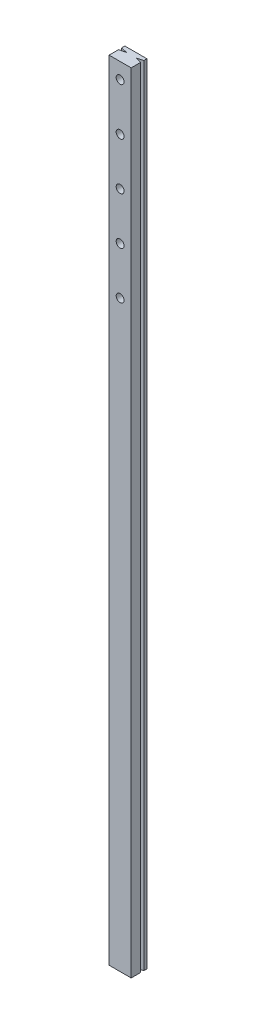
SolidWorks part; units mm, degrees
ref_plane "前视基准面" through (0, 0, 0) normal (0, 0, 1) x (1, 0, 0)
ref_plane "上视基准面" through (0, 0, 0) normal (0, 1, 0) x (1, 0, 0)
ref_plane "右视基准面" through (0, 0, 0) normal (1, 0, 0) x (0, 0, -1)
sketch "草图1" plane through (0, 0, 0) normal (0, 1, 0) x (1, 0, 0)
  line L0 (-89.2543, 0) -> (77.4586, 0) construction
  line L1 (0, 99.6738) -> (0, -95.7419) construction
  line L2 (-3.5, 1.5) -> (-1.5, 1)
  line L3 (-3.5, -2.5) -> (3.5, -2.5)
  line L4 (-3.5, -2.5) -> (-3.5, 0.5)
  line L5 (-3.5, 2.5) -> (3.5, 2.5)
  line L6 (3.5, -2.5) -> (3.5, 0.5)
  line L7 (-3.5, -2.5) -> (3.5, 2.5) construction
  line L8 (-3.5, 2.5) -> (3.5, -2.5) construction
  line L9 (-1.5, 1) -> (-3.5, 0.5)
  line L10 (1.5, 1) -> (3.5, 0.5)
  line L11 (3.5, 1.5) -> (1.5, 1)
  line L12 (-3.5, 1.5) -> (-3.5, 2.5)
  line L13 (3.5, 1.5) -> (3.5, 2.5)
  point P5 (0, 0)
  dimension "D1" = 7
  dimension "D2" = 5
  dimension "D3" = 1.5
  dimension "D4" = 3
  dimension "D5" = 2
  dimension "D6" = 0.5
extrude "凸台-拉伸1" add sketch "草图1" along normal blind 250
sketch "草图2" plane through (0, 0, -2.5) normal (0, 0, -1) x (-1, 0, 0)
  line L0 (0, 250) -> (0, 235.6045) construction
  line L1 (-3.5, 250) -> (3.5, 250) construction
  circle A1 centre (0, 245) radius 1.25
  dimension "D2" = 2.5
  dimension "D1" = 5
extrude "切除-拉伸3" cut sketch "草图2" against normal through all
pattern_linear "阵列(线性)1" count 5 spacing 15 along (0, -1, 0) of "切除-拉伸3"
